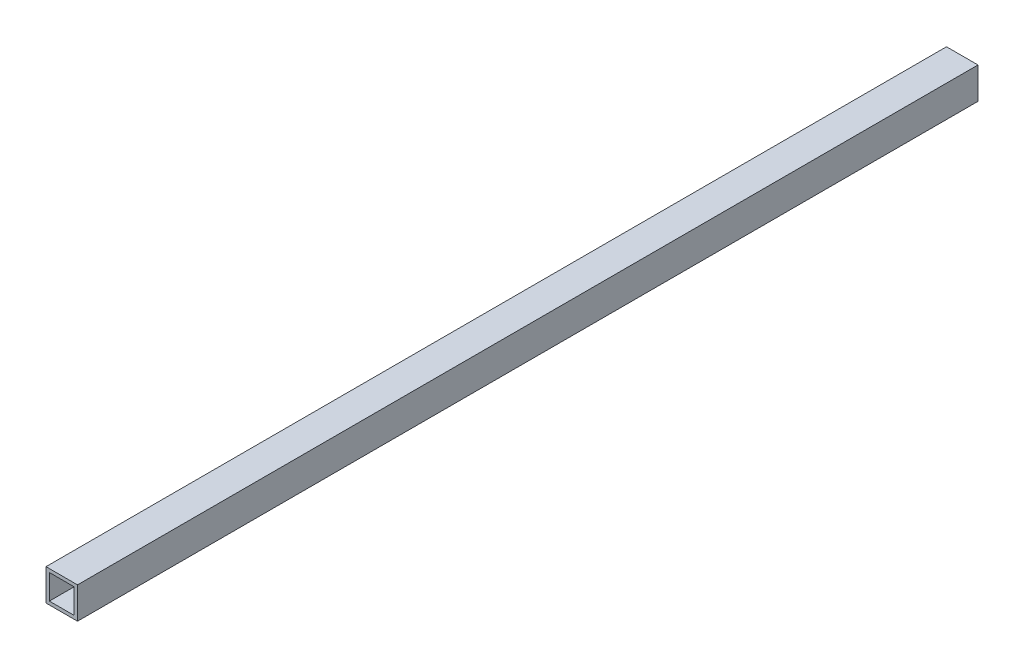
SolidWorks part; units mm, degrees
ref_plane "前视基准面" through (0, 0, 0) normal (0, 0, 1) x (1, 0, 0)
ref_plane "上视基准面" through (0, 0, 0) normal (0, 1, 0) x (1, 0, 0)
ref_plane "右视基准面" through (0, 0, 0) normal (1, 0, 0) x (0, 0, -1)
sketch "草图1" plane through (0, 0, 0) normal (0, 0, 1) x (1, 0, 0)
  line L1 (-5.5, 5.5) -> (5.5, 5.5)
  line L2 (-5.5, 5.5) -> (-5.5, -5.5)
  line L3 (-5.5, -5.5) -> (5.5, -5.5)
  line L4 (5.5, 5.5) -> (5.5, -5.5)
  line L5 (-5.5, 5.5) -> (5.5, -5.5) construction
  line L6 (-5.5, -5.5) -> (5.5, 5.5) construction
  point P0 (0, 0)
  dimension "D1" = 11
extrude "拉伸-薄壁1" add sketch "草图1" along normal blind 400 thin thin type one direction wall 1.5
